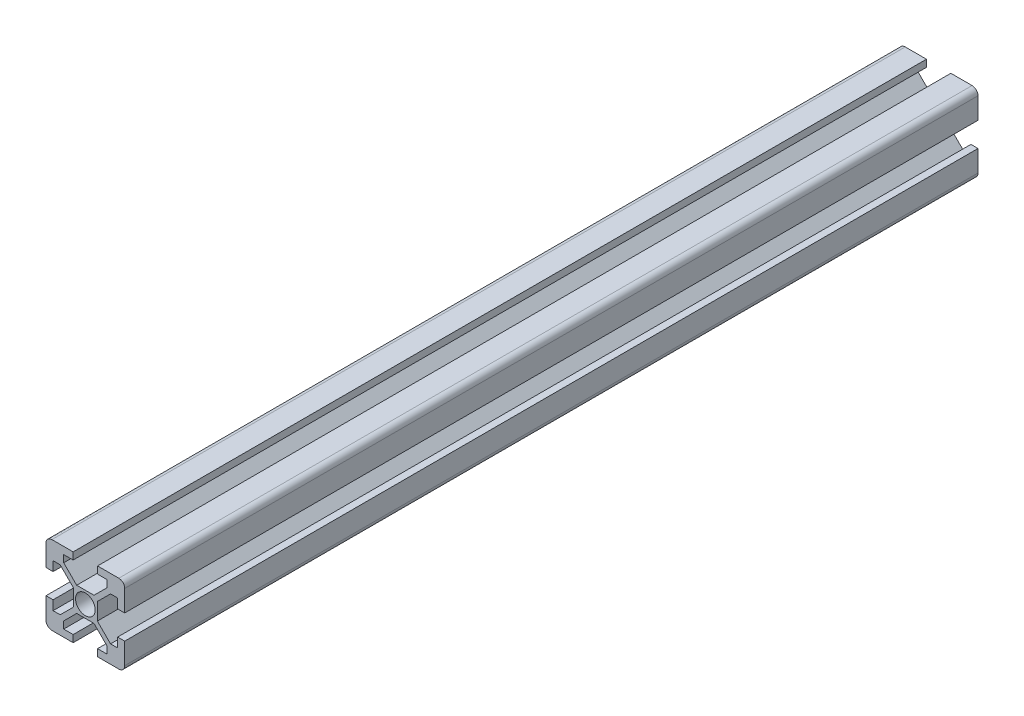
SolidWorks part; units mm, degrees
ref_plane "前视基准面" through (0, 0, 0) normal (0, 0, 1) x (1, 0, 0)
ref_plane "上视基准面" through (0, 0, 0) normal (0, 1, 0) x (1, 0, 0)
ref_plane "右视基准面" through (0, 0, 0) normal (1, 0, 0) x (0, 0, -1)
sketch "草图2" plane through (0, 0, 0) normal (0, 0, 1) x (1, 0, 0)
  line L0 (-10, -3.1) -> (-8.2, -3.1)
  line L1 (-8.5, 10) -> (8.5, 10)
  line L2 (-10, 8.5) -> (-10, -8.5)
  line L3 (-8.5, -10) -> (8.5, -10)
  line L4 (10, 8.5) -> (10, -8.5)
  line L5 (-10, 10) -> (10, -10) construction
  line L6 (-10, -10) -> (10, 10) construction
  line L7 (-3.0541, 3.1) -> (3.0541, 3.1)
  line L8 (-3.0541, 3.1) -> (-3.0541, -3.1)
  line L9 (-3.0541, -3.1) -> (3.0541, -3.1)
  line L10 (3.0541, 3.1) -> (3.0541, -3.1)
  line L11 (-3.0541, 3.1) -> (3.0541, -3.1) construction
  line L12 (-3.0541, -3.1) -> (3.0541, 3.1) construction
  line L13 (-8.2, -3.1) -> (-8.2, -5.5)
  line L14 (-8.2, -5.5) -> (-6.3971, -5.5)
  line L15 (-6.3971, -5.5) -> (-3.0541, -2.1571)
  line L16 (-5.5, 6.3971) -> (-2.1571, 3.0541)
  line L17 (-5.5, 8.2) -> (-5.5, 6.3971)
  line L18 (-3.1, 8.2) -> (-5.5, 8.2)
  line L19 (-3.1, 10) -> (-3.1, 8.2)
  line L20 (6.3971, 5.5) -> (3.0541, 2.1571)
  line L21 (8.2, 5.5) -> (6.3971, 5.5)
  line L22 (8.2, 3.1) -> (8.2, 5.5)
  line L23 (10, 3.1) -> (8.2, 3.1)
  line L24 (5.5, -6.3971) -> (2.1571, -3.0541)
  line L25 (5.5, -8.2) -> (5.5, -6.3971)
  line L26 (3.1, -8.2) -> (5.5, -8.2)
  line L27 (3.1, -10) -> (3.1, -8.2)
  line L28 (-3.1, -10) -> (-3.1, -8.2)
  line L29 (-3.1, -8.2) -> (-5.5, -8.2)
  line L30 (-5.5, -8.2) -> (-5.5, -6.3971)
  line L31 (-5.5, -6.3971) -> (-2.1571, -3.0541)
  line L32 (-8.2, 5.5) -> (-6.3971, 5.5)
  line L33 (-6.3971, 5.5) -> (-3.0541, 2.1571)
  line L34 (-8.2, 3.1) -> (-8.2, 5.5)
  line L35 (-10, 3.1) -> (-8.2, 3.1)
  line L36 (5.5, 8.2) -> (5.5, 6.3971)
  line L37 (5.5, 6.3971) -> (2.1571, 3.0541)
  line L38 (3.1, 8.2) -> (5.5, 8.2)
  line L39 (3.1, 10) -> (3.1, 8.2)
  line L40 (8.2, -5.5) -> (6.3971, -5.5)
  line L41 (6.3971, -5.5) -> (3.0541, -2.1571)
  line L42 (8.2, -3.1) -> (8.2, -5.5)
  line L43 (10, -3.1) -> (8.2, -3.1)
  circle A0 centre (0, 0) radius 2.5
  arc A1 (-10, 8.5) -> (-8.5, 10) centre (-8.5, 8.5) cw
  arc A2 (-10, -8.5) -> (-8.5, -10) centre (-8.5, -8.5) ccw
  arc A3 (8.5, 10) -> (10, 8.5) centre (8.5, 8.5) cw
  arc A4 (10, -8.5) -> (8.5, -10) centre (8.5, -8.5) cw
  point P0 (0, 0)
  point P19 (0, 0)
  point P25 (0, 0)
  point P31 (0, 0)
  point P37 (0, 0)
  point P59 (0, 0)
extrude "凸台-拉伸1" add sketch "草图2" along normal blind 216.86
